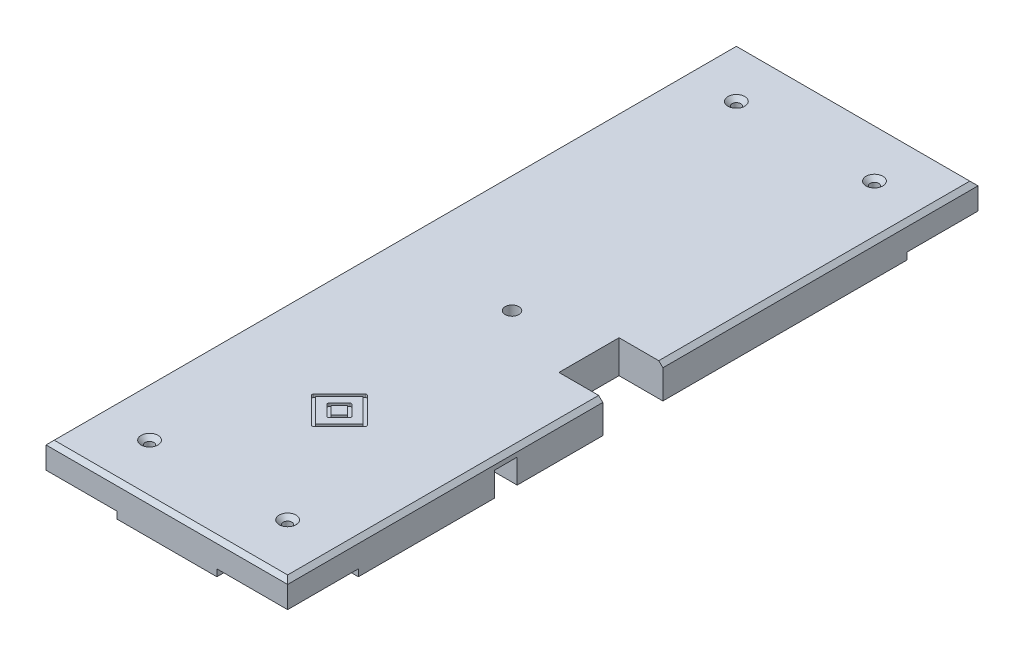
SolidWorks part; units mm, degrees
ref_plane "Front Plane" through (0, 0, 0) normal (0, 0, 1) x (1, 0, 0)
ref_plane "Top Plane" through (0, 0, 0) normal (0, 1, 0) x (1, 0, 0)
ref_plane "Right Plane" through (0, 0, 0) normal (1, 0, 0) x (0, 0, -1)
sketch "Sketch1" plane through (0, -20.7207, 0) normal (0, 1, 0) x (1, 0, 0)
  line L3 (6.005, -235.0339) -> (6.005, -194.0339)
  line L4 (6.005, -194.0339) -> (47.005, -194.0339)
  line L12 (47.005, 123.9661) -> (6.005, 123.9661)
  line L13 (47.005, -194.0339) -> (47.005, 123.9661)
  line L14 (6.005, -194.0339) -> (47.005, -194.0339)
  line L15 (6.005, -235.0339) -> (6.005, -194.0339)
  line L16 (-51.995, -235.0339) -> (6.005, -235.0339)
  line L17 (-51.995, -194.0339) -> (-51.995, -235.0339)
  line L18 (-92.995, -194.0339) -> (-51.995, -194.0339)
  line L19 (-92.995, 123.9661) -> (-92.995, -194.0339)
  line L20 (-51.995, 123.9661) -> (-92.995, 123.9661)
  line L21 (-51.995, 164.9661) -> (-51.995, 123.9661)
  line L22 (6.005, 164.9661) -> (-51.995, 164.9661)
  line L23 (6.005, 123.9661) -> (6.005, 164.9661)
  line L24 (47.005, 123.9661) -> (6.005, 123.9661)
  line L25 (47.005, -194.0339) -> (47.005, 123.9661)
  line L28 (-51.995, -235.0339) -> (6.005, -235.0339)
  line L29 (-51.995, -194.0339) -> (-51.995, -235.0339)
  line L30 (-92.995, -194.0339) -> (-51.995, -194.0339)
  line L31 (-92.995, 123.9661) -> (-92.995, -194.0339)
  line L32 (-51.995, 123.9661) -> (-92.995, 123.9661)
  line L33 (-51.995, 164.9661) -> (-51.995, 123.9661)
  line L34 (6.005, 164.9661) -> (-51.995, 164.9661)
  line L35 (6.005, 123.9661) -> (6.005, 164.9661)
  circle A1 centre (17.005, -225.0339) radius 2.5
  circle A2 centre (17.005, -225.0339) radius 2.5
  circle A3 centre (37.005, -205.0339) radius 2.5
  circle A4 centre (37.005, -205.0339) radius 2.5
  circle A5 centre (17.005, -205.0339) radius 2.5
  circle A6 centre (17.005, -205.0339) radius 2.5
  circle A7 centre (-62.995, -205.0339) radius 2.5
  circle A8 centre (-62.995, -205.0339) radius 2.5
  circle A9 centre (-62.995, -225.0339) radius 2.5
  circle A10 centre (-62.995, -225.0339) radius 2.5
  circle A11 centre (-82.995, -225.0339) radius 2.5
  circle A12 centre (-82.995, -225.0339) radius 2.5
  circle A13 centre (-82.995, -205.0339) radius 2.5
  circle A14 centre (-82.995, -205.0339) radius 2.5
  circle A15 centre (-62.995, 134.9661) radius 2.5
  circle A16 centre (-62.995, 134.9661) radius 2.5
  circle A17 centre (-62.995, 154.9661) radius 2.5
  circle A18 centre (-62.995, 154.9661) radius 2.5
  circle A19 centre (-82.995, 154.9661) radius 2.5
  circle A20 centre (-82.995, 154.9661) radius 2.5
  circle A21 centre (37.005, 134.9661) radius 2.5
  circle A22 centre (37.005, 134.9661) radius 2.5
  circle A23 centre (17.005, 134.9661) radius 2.5
  circle A24 centre (17.005, 134.9661) radius 2.5
  circle A25 centre (17.005, 154.9661) radius 2.5
  circle A26 centre (17.005, 154.9661) radius 2.5
  circle A27 centre (37.005, 154.9661) radius 2.5
  circle A28 centre (37.005, 154.9661) radius 2.5
  circle A29 centre (-82.995, 134.9661) radius 2.5
  circle A30 centre (-82.995, 134.9661) radius 2.5
  dimension "D1" = 0
  dimension "D2" = 0
  dimension "D3" = 0
  dimension "D4" = 0
  dimension "D5" = 0
  dimension "D6" = 0
  dimension "D7" = 0
  dimension "D8" = 0
  dimension "D9" = 0
  dimension "D10" = 0
  dimension "D11" = 0
  dimension "D12" = 0
  dimension "D13" = 0
  dimension "D14" = 0
  dimension "D15" = 0
  dimension "D16" = 0
extrude "Boss-Extrude1" add sketch "Sketch1" against normal up to surface (4 mm away) contours L31 L30 L29 L28 L3 L4 L25 L24 L35 L34 L33 L32
sketch "Sketch2" plane through (0, -20.7207, 0) normal (0, 1, 0) x (1, 0, 0)
  line L0 (-92.995, 164.9661) -> (47.005, 164.9661)
  line L1 (-92.995, 164.9661) -> (-92.995, -235.0339)
  line L2 (47.005, 164.9661) -> (47.005, -235.0339)
  line L3 (-92.995, -235.0339) -> (47.005, -235.0339)
  line L4 (-52.995, -235.0339) -> (-92.995, -235.0339) construction
extrude "Boss-Extrude2" add sketch "Sketch2" along normal blind 15.05
sketch "Sketch3" plane through (0, -20.7207, 0) normal (0, -1, 0) x (1, 0, 0)
  line L0 (-56.995, 225.0339) -> (-86.995, 225.0339) construction
  line L1 (-86.995, 229.0339) -> (-78.995, 229.0339)
  line L2 (-86.995, 229.0339) -> (-86.995, 199.0339)
  line L3 (-86.995, 199.0339) -> (-78.995, 199.0339)
  line L4 (-78.995, 229.0339) -> (-78.995, 199.0339)
  line L5 (-56.995, 221.0339) -> (-86.995, 221.0339)
  line L6 (-56.995, 221.0339) -> (-56.995, 229.0339)
  line L7 (-56.995, 229.0339) -> (-86.995, 229.0339)
  line L8 (-86.995, 221.0339) -> (-86.995, 229.0339)
  line L9 (-82.995, 229.0339) -> (-82.995, 199.0339) construction
  line L10 (-22.995, 235.0339) -> (-22.995, 201.9743) construction
  line L11 (6.005, 235.0339) -> (-51.995, 235.0339) construction
  line L12 (-92.995, 35.0339) -> (-2.995, 35.0339) construction
  line L13 (-92.995, 194.0339) -> (-92.995, -123.9661) construction
  line L14 (41.005, 199.0339) -> (33.005, 199.0339)
  line L15 (41.005, 229.0339) -> (41.005, 199.0339)
  line L16 (33.005, 229.0339) -> (33.005, 199.0339)
  line L17 (11.005, 221.0339) -> (11.005, 229.0339)
  line L18 (11.005, 221.0339) -> (41.005, 221.0339)
  line L19 (11.005, 229.0339) -> (41.005, 229.0339)
  line L20 (-22.995, -164.9661) -> (-22.995, -131.9065) construction
  line L21 (-82.995, -158.9661) -> (-82.995, -128.9661) construction
  line L22 (-56.995, -154.9661) -> (-86.995, -154.9661) construction
  line L23 (11.005, -158.9661) -> (41.005, -158.9661)
  line L24 (11.005, -150.9661) -> (41.005, -150.9661)
  line L25 (11.005, -150.9661) -> (11.005, -158.9661)
  line L26 (33.005, -158.9661) -> (33.005, -128.9661)
  line L27 (41.005, -158.9661) -> (41.005, -128.9661)
  line L28 (41.005, -128.9661) -> (33.005, -128.9661)
  line L29 (-86.995, -150.9661) -> (-86.995, -158.9661)
  line L30 (-56.995, -158.9661) -> (-86.995, -158.9661)
  line L31 (-56.995, -150.9661) -> (-56.995, -158.9661)
  line L32 (-56.995, -150.9661) -> (-86.995, -150.9661)
  line L33 (-78.995, -158.9661) -> (-78.995, -128.9661)
  line L34 (-86.995, -128.9661) -> (-78.995, -128.9661)
  line L35 (-86.995, -158.9661) -> (-86.995, -128.9661)
  line L36 (-86.995, -158.9661) -> (-78.995, -158.9661)
  circle A0 centre (-82.995, 225.0339) radius 2.5 construction
  circle A1 centre (-82.995, 225.0339) radius 2.5
  circle A2 centre (-82.995, -154.9661) radius 2.5
  dimension "D1" = 8
  dimension "D2" = 8
  dimension "D3" = 30
  dimension "D4" = 30
extrude "Cut-Extrude1" cut sketch "Sketch3" against normal blind 5 contours L18 L16 L14 L15 | L19 L16 L18 L15 | L19 L17 L18 L16 | L6 L7 L4 L5 | L4 L5 L2 L3 | L5 L4 L1 L2 A1 | A1 | L33 L30 L31 L32 | L35 L32 L33 L34 | L30 L33 L32 L29 A2 | A2 | L23 L27 L24 L26 | L23 L26 L24 L25 | L27 L28 L26 L24
sketch "Sketch4" plane through (0, -20.7207, 0) normal (0, -1, 0) x (1, 0, 0)
  line L0 (-92.995, 235.0339) -> (47.005, -164.9661) construction
  line L2 (47.005, 235.0339) -> (-92.995, -164.9661) construction
  line L3 (-22.995, 35.0339) -> (-22.995, 293.1624) construction
  circle A0 centre (-62.995, -134.9661) radius 2.5 construction
  circle A1 centre (-62.995, -134.9661) radius 2.5
  circle A5 centre (17.005, -134.9661) radius 2.5
  circle A9 centre (-62.995, 205.0339) radius 2.5
  circle A10 centre (17.005, 205.0339) radius 2.5
  point P9 (0, 0)
  point P16 (0, 0)
extrude "Cut-Extrude2" cut sketch "Sketch4" against normal up to next
chamfer "Chamfer1" distance 2.38 8 edges at (-62.995, -5.6707, -132.4661) (17.005, -5.6707, -132.4661) (-22.995, -5.6707, -164.9661) (47.005, -5.6707, 35.0339) (-22.995, -5.6707, 235.0339) (-92.995, -5.6707, 35.0339) (-62.995, -5.6707, 207.5339) (17.005, -5.6707, 207.5339)
sketch "Sketch5" plane through (0, -5.6707, 0) normal (0, 1, 0) x (1, 0, 0)
  line L0 (47.005, -35.0339) -> (-92.995, -35.0339) construction
  line L1 (47.005, -235.0339) -> (47.005, 164.9661) construction
  line L2 (-92.995, 164.9661) -> (-92.995, -235.0339) construction
  line L3 (47.005, 164.9661) -> (-92.995, -235.0339) construction
  line L4 (47.005, -235.0339) -> (-92.995, 164.9661) construction
  circle A0 centre (-22.995, -35.0339) radius 4
  point P2 (0, 0)
  point P15 (-22.995, -35.0339)
  point P16 (0, 0)
  point P17 (0, 0)
  point P18 (0, 0)
  point P19 (0, 0)
  point P20 (0, 0)
  point P21 (0, 0)
  dimension "D1" = 8
extrude "Cut-Extrude3" cut sketch "Sketch5" against normal up to next contours A0
sketch "Sketch6" plane through (0, -5.6707, 0) normal (0, 1, 0) x (1, 0, 0)
  line L0 (-22.995, -35.0339) -> (-22.995, -135.0339) construction
  line L1 (-22.995, -120.0339) -> (-22.995, -135.0339) construction
  line L2 (-22.995, -135.0339) -> (-7.995, -135.0339) construction
  line L3 (-29.0147, -135.0339) -> (-22.995, -129.0141) construction
  line L4 (-28.396, -135.6526) -> (-22.3762, -129.6328)
  line L5 (-92.995, 164.9661) -> (47.005, -235.0339) construction
  line L6 (47.005, 164.9661) -> (-92.995, -235.0339) construction
  line L9 (-29.6334, -134.4151) -> (-23.6137, -128.3954)
  line L10 (-22.995, -120.0339) -> (-37.995, -135.0339) construction
  line L13 (-22.3762, -120.6526) -> (-37.3762, -135.6526)
  line L14 (-23.6137, -119.4151) -> (-38.6137, -134.4151)
  line L19 (-16.9752, -135.0339) -> (-22.995, -141.0536) construction
  line L20 (-17.5939, -134.4151) -> (-23.6137, -140.4349)
  line L21 (-16.3565, -135.6526) -> (-22.3762, -141.6723)
  line L24 (-23.6137, -120.6526) -> (-8.6137, -135.6526)
  line L25 (-22.3762, -119.4151) -> (-7.3762, -134.4151)
  line L26 (-29.0147, -135.0339) -> (-22.995, -141.0536) construction
  line L27 (-22.995, -120.0339) -> (-7.995, -135.0339) construction
  line L28 (-28.396, -134.4151) -> (-22.3762, -140.4349)
  line L33 (-29.6334, -135.6526) -> (-23.6137, -141.6723)
  line L34 (-22.995, -150.0339) -> (-37.995, -135.0339) construction
  line L39 (-22.3762, -149.4151) -> (-37.3762, -134.4151)
  line L42 (-23.6137, -150.6526) -> (-38.6137, -135.6526)
  line L43 (-22.995, -150.0339) -> (-7.995, -135.0339) construction
  line L46 (-16.3565, -134.4151) -> (-22.3762, -128.3954)
  line L47 (-17.5939, -135.6526) -> (-23.6137, -129.6328)
  line L50 (-16.9752, -135.0339) -> (-22.995, -129.0141) construction
  line L51 (-23.6137, -149.4151) -> (-8.6137, -134.4151)
  line L52 (-22.3762, -150.6526) -> (-7.3762, -135.6526)
  arc A11 (-7.3762, -134.4151) -> (-8.6137, -135.6526) centre (-7.995, -135.0339) cw
  arc A12 (-23.6137, -120.6526) -> (-22.3762, -119.4151) centre (-22.995, -120.0339) cw
  arc A21 (-17.5939, -135.6526) -> (-16.3565, -134.4151) centre (-16.9752, -135.0339) ccw
  arc A22 (-22.3762, -128.3954) -> (-23.6137, -129.6328) centre (-22.995, -129.0141) ccw
  arc A23 (-28.396, -135.6526) -> (-29.6334, -134.4151) centre (-29.0147, -135.0339) cw
  arc A24 (-23.6137, -128.3954) -> (-22.3762, -129.6328) centre (-22.995, -129.0141) cw
  arc A25 (-22.3762, -120.6526) -> (-23.6137, -119.4151) centre (-22.995, -120.0339) ccw
  arc A26 (-38.6137, -134.4151) -> (-37.3762, -135.6526) centre (-37.995, -135.0339) ccw
  arc A27 (-17.5939, -134.4151) -> (-16.3565, -135.6526) centre (-16.9752, -135.0339) cw
  arc A28 (-22.3762, -141.6723) -> (-23.6137, -140.4349) centre (-22.995, -141.0536) cw
  arc A29 (-28.396, -134.4151) -> (-29.6334, -135.6526) centre (-29.0147, -135.0339) ccw
  arc A30 (-23.6137, -141.6723) -> (-22.3762, -140.4349) centre (-22.995, -141.0536) ccw
  arc A31 (-22.3762, -149.4151) -> (-23.6137, -150.6526) centre (-22.995, -150.0339) cw
  arc A32 (-38.6137, -135.6526) -> (-37.3762, -134.4151) centre (-37.995, -135.0339) cw
  arc A33 (-23.6137, -149.4151) -> (-22.3762, -150.6526) centre (-22.995, -150.0339) ccw
  arc A34 (-7.3762, -135.6526) -> (-8.6137, -134.4151) centre (-7.995, -135.0339) ccw
  point P1 (-22.995, -184.1691)
  point P9 (0, 0)
  point P10 (0, 0)
  point P11 (0, 0)
  point P12 (0, 0)
  point P13 (-23.6137, -226.5061)
  point P14 (-23.6137, -318.6587)
  point P17 (-26.0048, -132.024)
  point P23 (-30.495, -127.5339)
  point P30 (-19.9851, -138.0437)
  point P37 (-26.0048, -138.0437)
  point P46 (-30.495, -142.5339)
  point P48 (-15.495, -127.5339)
  point P57 (-15.495, -142.5339)
  point P82 (-19.9851, -132.024)
  dimension "D4" = 4.6
  dimension "D6" = 8.5132
  dimension "D1" = 21.2132
  dimension "D2" = 8.9803
  dimension "D3" = 1.75
  dimension "D7" = 15
  dimension "D5" = 1.75
  dimension "D8" = 100
extrude "Cut-Extrude4" cut sketch "Sketch6" against normal blind 1.75
sketch "Sketch7" plane through (0, -24.7207, 0) normal (0, -1, 0) x (1, 0, 0)
  line L1 (-0.995, 168.0339) -> (-44.995, 168.0339)
  line L2 (-0.995, 168.0339) -> (-0.995, 102.0339)
  line L3 (-0.995, 102.0339) -> (-44.995, 102.0339)
  line L5 (-44.995, 168.0339) -> (-44.995, 102.0339)
  line L6 (-0.995, 168.0339) -> (-44.995, 102.0339) construction
  line L7 (-0.995, 102.0339) -> (-44.995, 168.0339) construction
  line L10 (-0.995, 115.0339) -> (49.005, 115.0339)
  line L11 (-0.995, 115.0339) -> (-0.995, 102.0339)
  line L12 (-92.995, -123.9661) -> (-51.995, -123.9661)
  line L13 (-51.995, -123.9661) -> (-51.995, -164.9661)
  line L14 (-51.995, -164.9661) -> (6.005, -164.9661)
  line L15 (6.005, -164.9661) -> (6.005, -123.9661)
  line L16 (6.005, -123.9661) -> (47.005, -123.9661)
  line L17 (47.005, -123.9661) -> (47.005, 194.0339)
  line L18 (47.005, 194.0339) -> (6.005, 194.0339)
  line L19 (47.005, 194.0339) -> (6.005, 194.0339)
  line L20 (6.005, 235.0339) -> (-51.995, 235.0339)
  line L21 (-51.995, 235.0339) -> (-51.995, 194.0339)
  line L22 (-51.995, 194.0339) -> (-92.995, 194.0339)
  line L23 (-92.995, 194.0339) -> (-92.995, -123.9661)
  line L24 (-92.995, -123.9661) -> (-51.995, -123.9661)
  line L25 (-51.995, -123.9661) -> (-51.995, -164.9661)
  line L26 (-51.995, -164.9661) -> (6.005, -164.9661)
  line L27 (6.005, -164.9661) -> (6.005, -123.9661)
  line L28 (6.005, -123.9661) -> (47.005, -123.9661)
  line L29 (47.005, -123.9661) -> (47.005, 194.0339)
  line L32 (6.005, 235.0339) -> (-51.995, 235.0339)
  line L33 (-51.995, 235.0339) -> (-51.995, 194.0339)
  line L34 (-51.995, 194.0339) -> (-92.995, 194.0339)
  line L35 (-92.995, 194.0339) -> (-92.995, -123.9661)
  line L38 (-0.995, 102.0339) -> (49.005, 102.0339)
  line L39 (49.005, 115.0339) -> (49.005, 102.0339)
  line L55 (6.005, 194.0339) -> (6.005, 235.0339)
  line L56 (6.005, 194.0339) -> (6.005, 235.0339)
  point P2 (-22.995, 135.0339)
  point P8 (-22.995, 135.0339)
  point P20 (-3.6137, 160.0339)
  point P22 (-3.6137, 160.0339)
  point P23 (-3.6137, 160.0339)
  point P24 (0, 0)
  point P25 (-3.6137, 160.0339)
  point P26 (0, 0)
  point P78 (-3.6137, 160.0339)
  dimension "D2" = 44
  dimension "D3" = 66
  dimension "D4" = 50
  dimension "D5" = 13
  dimension "D1" = 0
extrude "Cut-Extrude5" cut sketch "Sketch7" along direction (0, -1, 0) on the side against the normal offset from surface (14.05 mm away) 5 contours L5 L3 L2 L1 | L11 L10 L39 L38
sketch "Sketch8" plane through (0, -5.6707, 0) normal (0, 1, 0) x (1, 0, 0)
  line L0 (47.005, -35.0339) -> (-93.7041, -35.0339) construction
  line L1 (47.005, -235.0339) -> (47.005, 164.9661) construction
  line L3 (21.6131, -52.445) -> (47.005, -52.445)
  line L4 (21.6131, -52.445) -> (21.6131, -17.6228)
  line L5 (21.6131, -17.6228) -> (47.005, -17.6228)
  line L6 (47.005, -52.445) -> (47.005, -17.6228)
  line L7 (21.6131, -52.445) -> (47.005, -17.6228) construction
  line L8 (21.6131, -17.6228) -> (47.005, -52.445) construction
  point P4 (34.3091, -35.0339)
extrude "Cut-Extrude6" cut sketch "Sketch8" against normal up to next
